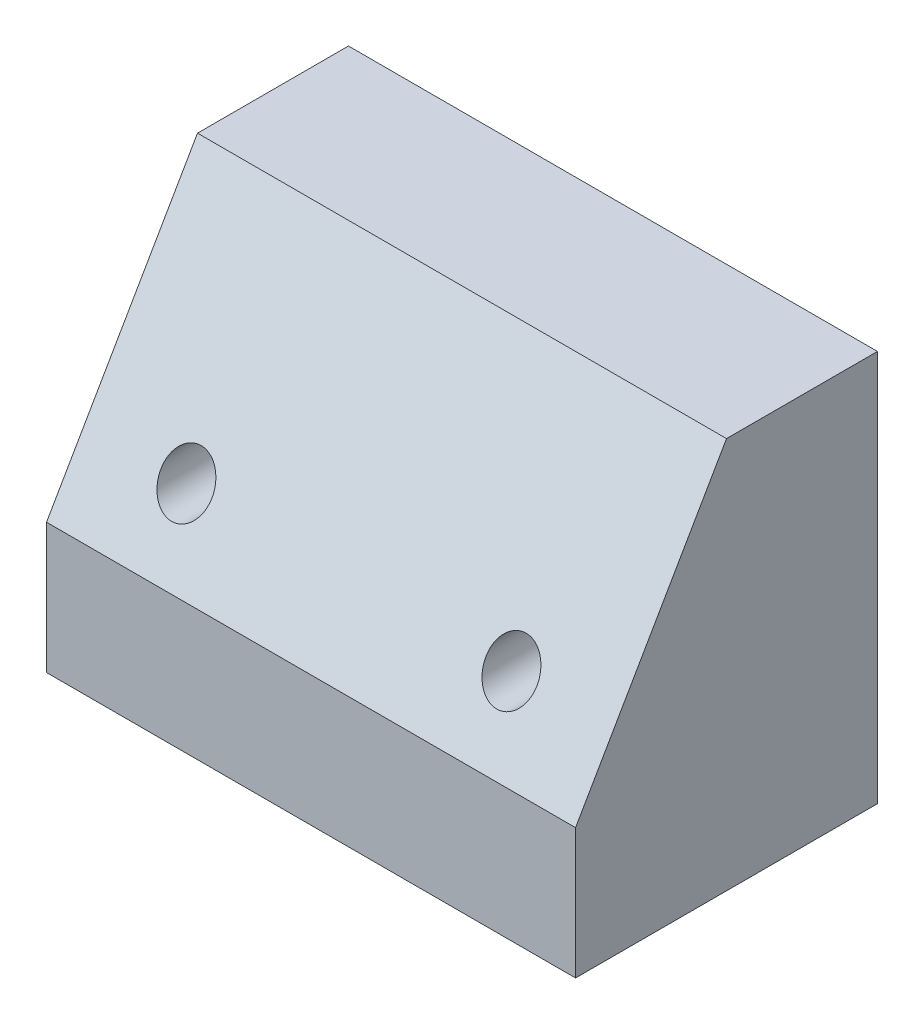
SolidWorks part; units mm, degrees
ref_plane "Ebene vorne" through (0, 0, 0) normal (0, 0, 1) x (1, 0, 0)
ref_plane "Ebene oben" through (0, 0, 0) normal (0, 1, 0) x (1, 0, 0)
ref_plane "Ebene rechts" through (0, 0, 0) normal (1, 0, 0) x (0, 0, -1)
sketch "Skizze1" plane through (0, 0, 0) normal (0, 0, 1) x (1, 0, 0)
  line L1 (77.8, -57.6) -> (-77.8, -57.6)
  line L2 (77.8, -57.6) -> (77.8, 57.6)
  line L3 (77.8, 57.6) -> (-77.8, 57.6)
  line L4 (-77.8, -57.6) -> (-77.8, 57.6)
  line L5 (77.8, -57.6) -> (-77.8, 57.6) construction
  line L6 (77.8, 57.6) -> (-77.8, -57.6) construction
  point P0 (0, 0)
  dimension "D1" = 115.2
  dimension "D2" = 155.6
extrude "Aufsatz-Linear austragen1" add sketch "Skizze1" along normal blind 88.8
hole_wizard "Stirnsenkung für M8 Senkschraube (Kopf Button)1" positions "Skizze4" profile "Skizze5" counterbore size "M8" standard "ANSI Metrisch" end condition through all
sketch "Skizze4" plane through (0, 0, 88.8) normal (0, 0, 1) x (1, 0, 0)
  line L0 (77.8, 57.6) -> (-77.8, 57.6) construction
  line L1 (-77.8, 57.6) -> (-77.8, -57.6) construction
  point P0 (-47.8, 0)
  dimension "D1" = 57.6
  dimension "D2" = 30
sketch "Skizze5" plane through (-47.8, 0, 88.8) normal (1, 0, 0) x (0, -1, 0)
  line L0 (0, 0) -> (0, 88.8)
  line L1 (0, 88.8) -> (4.5, 88.8)
  line L3 (4.5, 88.8) -> (4.5, 80)
  line L4 (4.5, 80) -> (7.5, 80)
  line L5 (7.5, 80) -> (7.5, 0)
  line L7 (7.5, 0) -> (0, 0)
  line L11 (0, -6.35) -> (0, 107.95) construction
  dimension "Bohrerdurchmesser" = 9
  dimension "Bohrungstiefe" = 88.8
  dimension "Senkdurchmesser2" = 15
  dimension "Senktiefe2" = 80
mirror "Spiegeln1" about plane through (0, 0, 0) normal (1, 0, 0) of "Stirnsenkung für M8 Senkschraube (Kopf Button)1"
sketch "Skizze6" plane through (-77.8, 0, 0) normal (-1, 0, 0) x (0, 0, 1)
  line L0 (44.4, 57.6) -> (88.8, -19.3031)
  line L1 (88.8, 57.6) -> (0, 57.6) construction
  line L2 (88.8, 57.6) -> (88.8, -57.6) construction
  line L3 (88.8, -19.3031) -> (88.8, 57.6)
  line L4 (88.8, 57.6) -> (44.4, 57.6)
  dimension "D1" = 88.8
  dimension "D2" = 60
extrude "Schnitt-Linear austragen1" cut sketch "Skizze6" against normal through all
